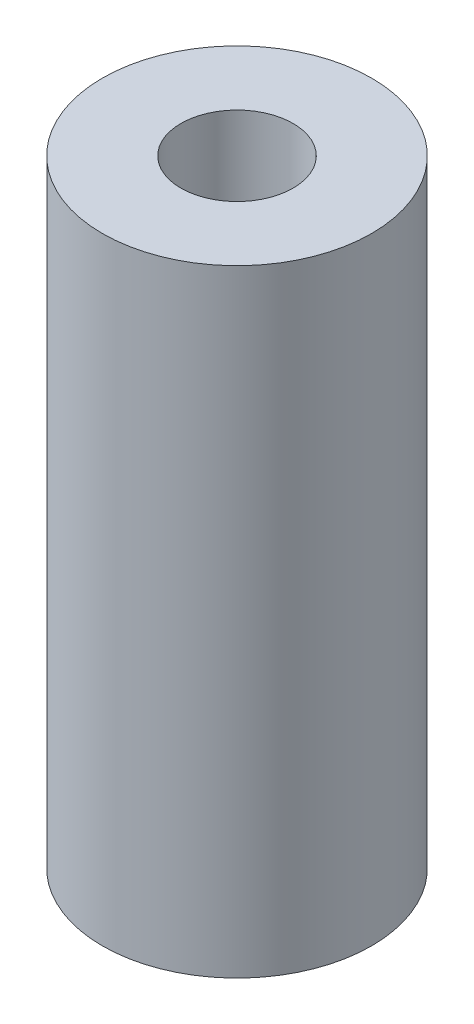
SolidWorks part; units mm, degrees
ref_plane "Front Plane" through (0, 0, 0) normal (0, 0, 1) x (1, 0, 0)
ref_plane "Top Plane" through (0, 0, 0) normal (0, 1, 0) x (1, 0, 0)
ref_plane "Right Plane" through (0, 0, 0) normal (1, 0, 0) x (0, 0, -1)
sketch "Sketch1" plane through (0, 0, 0) normal (0, 1, 0) x (1, 0, 0)
  circle A0 centre (0, 0) radius 6
  circle A1 centre (0, 0) radius 2.5
  dimension "D1" = 12
  dimension "D2" = 5
extrude "Boss-Extrude1" add sketch "Sketch1" along normal blind 27.5
